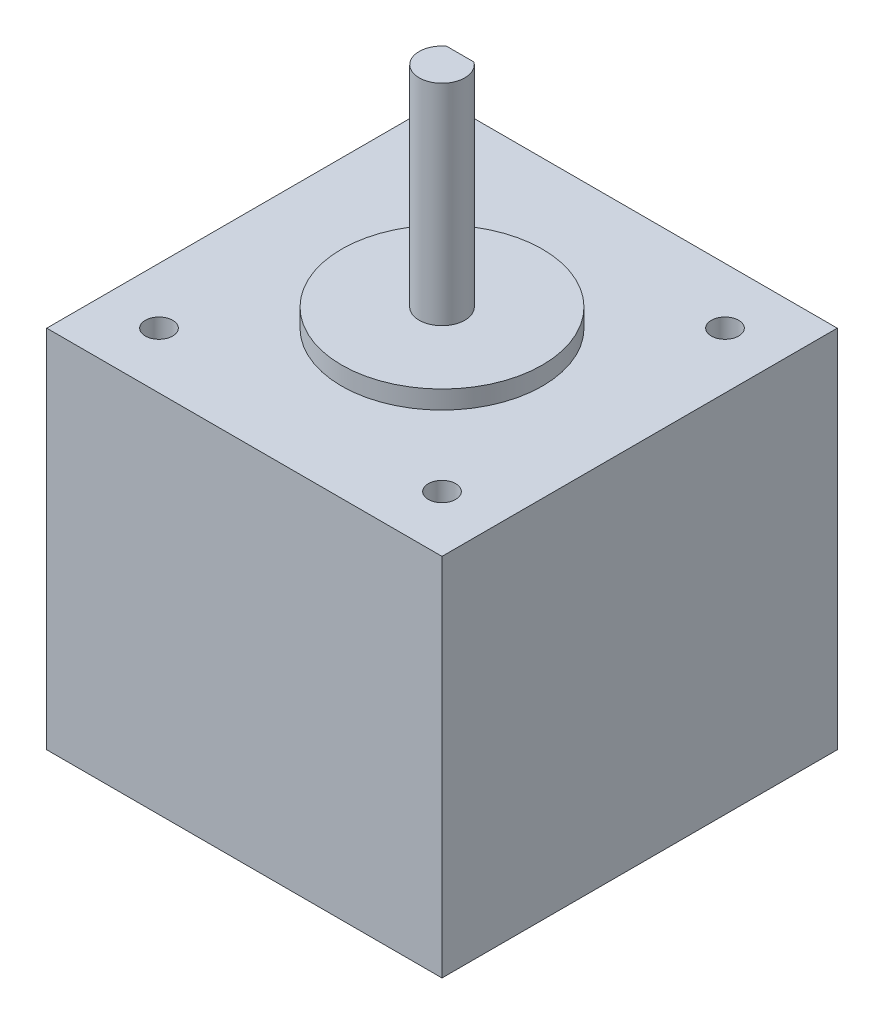
SolidWorks part; units mm, degrees
ref_plane "Front Plane" through (0, 0, 0) normal (0, 0, 1) x (1, 0, 0)
ref_plane "Top Plane" through (0, 0, 0) normal (0, 1, 0) x (1, 0, 0)
ref_plane "Right Plane" through (0, 0, 0) normal (1, 0, 0) x (0, 0, -1)
sketch "Sketch1" plane through (0, 0, 0) normal (0, 1, 0) x (1, 0, 0)
  line L1 (-21.65, 21.65) -> (21.65, 21.65)
  line L2 (-21.65, 21.65) -> (-21.65, -21.65)
  line L3 (-21.65, -21.65) -> (21.65, -21.65)
  line L4 (21.65, 21.65) -> (21.65, -21.65)
  line L5 (-21.65, 21.65) -> (21.65, -21.65) construction
  line L6 (-21.65, -21.65) -> (21.65, 21.65) construction
  point P0 (0, 0)
  dimension "D1" = 43.3
extrude "Boss-Extrude1" add sketch "Sketch1" along normal blind 40
sketch "Sketch2" plane through (0, 40, 0) normal (0, 1, 0) x (1, 0, 0)
  circle A0 centre (0, 0) radius 11
  dimension "D1" = 22
extrude "Boss-Extrude2" add sketch "Sketch2" along normal blind 2
sketch "Sketch3" plane through (0, 40, 0) normal (0, 1, 0) x (1, 0, 0)
  circle A0 centre (0, 0) radius 2.5
  dimension "D1" = 5
extrude "Boss-Extrude3" add sketch "Sketch3" along normal blind 25
sketch "Sketch4" plane through (0, 0, 0) normal (1, 0, 0) x (0, 0, -1)
  line L0 (-2.5, 65) -> (-2.5, 42) construction
  line L1 (2, 50) -> (2.5, 50)
  line L2 (2, 50) -> (2, 65)
  line L3 (2, 65) -> (2.5, 65)
  line L4 (2.5, 50) -> (2.5, 65)
  line L5 (2, 50) -> (2.5, 65) construction
  line L6 (2, 65) -> (2.5, 50) construction
  point P0 (2.25, 57.5)
  point P5 (2.25, 65)
  point P7 (0.6001, 44.9283)
  point P8 (2.25, 65)
  dimension "D1" = 15
  dimension "D2" = 4.5
extrude "Cut-Extrude1" cut sketch "Sketch4" against normal through all both and the other way through all
sketch "Sketch5" plane through (0, 40, 0) normal (0, 1, 0) x (1, 0, 0)
  line L2 (-15.5, -15.5) -> (15.5, -15.5) construction
  line L4 (-15.5, -15.5) -> (-15.5, 15.5) construction
  line L5 (-15.5, 15.5) -> (15.5, 15.5) construction
  line L6 (15.5, -15.5) -> (15.5, 15.5) construction
  line L7 (-15.5, -15.5) -> (15.5, 15.5) construction
  line L8 (-15.5, 15.5) -> (15.5, -15.5) construction
  circle A2 centre (15.5, 15.5) radius 1.5
  circle A3 centre (15.5, -15.5) radius 1.5
  circle A4 centre (-15.5, -15.5) radius 1.5
  circle A5 centre (-15.5, 15.5) radius 1.5
  point P0 (0, 0)
  dimension "D2" = 3
  dimension "D1" = 31
extrude "Cut-Extrude2" cut sketch "Sketch5" against normal blind 4.5
